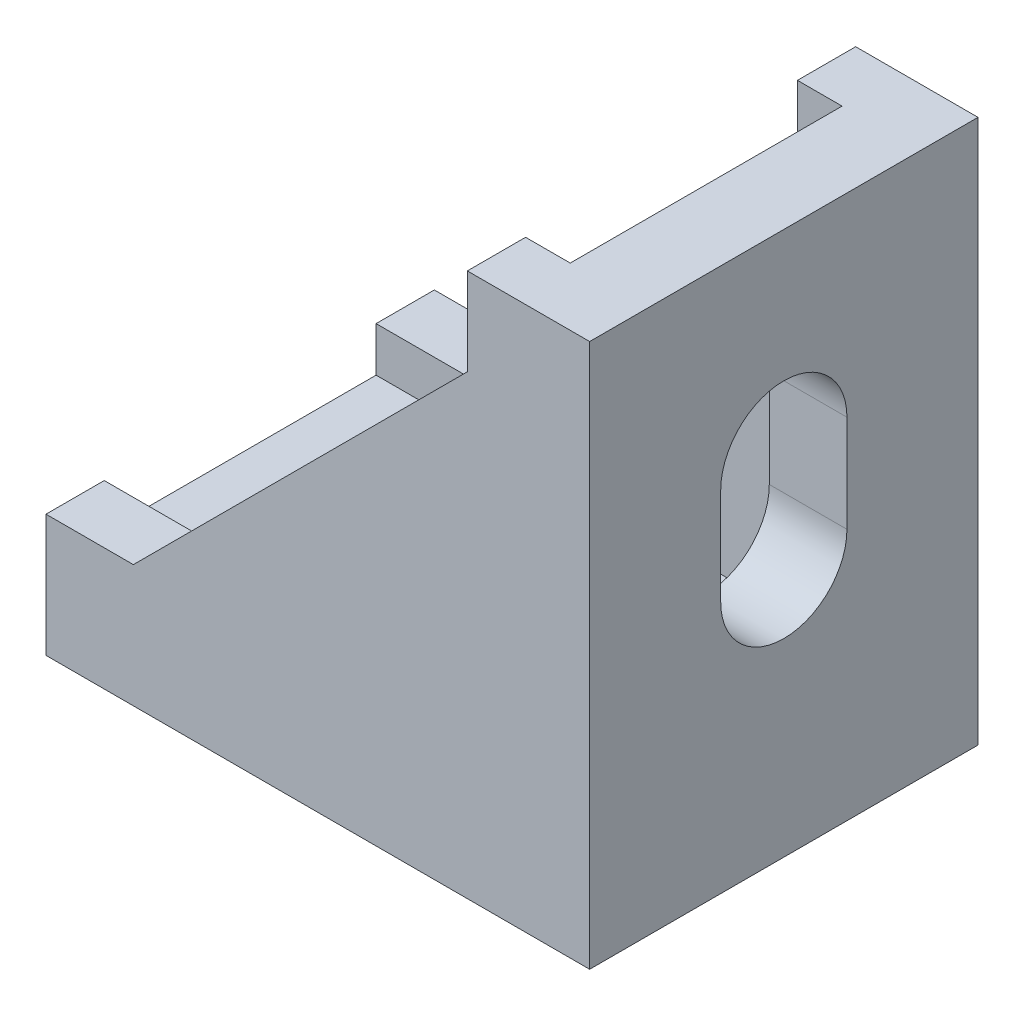
SolidWorks part; units mm, degrees
ref_plane "前视基准面" through (0, 0, 0) normal (0, 0, 1) x (1, 0, 0)
ref_plane "上视基准面" through (0, 0, 0) normal (0, 1, 0) x (1, 0, 0)
ref_plane "右视基准面" through (0, 0, 0) normal (1, 0, 0) x (0, 0, -1)
sketch "草图1" plane through (0, 0, 0) normal (0, 0, 1) x (1, 0, 0)
  line L1 (14, -14) -> (-14, -14)
  line L2 (14, -14) -> (14, 14)
  line L3 (14, 14) -> (10, 14)
  line L4 (-14, -14) -> (-14, -10)
  line L10 (10, 14) -> (10, -10)
  line L11 (10, -10) -> (-14, -10)
  point P0 (0, 0)
  dimension "D2" = 28
  dimension "D4" = 4
  dimension "D3" = 4
extrude "凸台-拉伸1" add sketch "草图1" along normal blind 20
sketch "草图3" plane through (0, 0, 0) normal (0, 0, -1) x (-1, 0, 0)
  line L0 (-10, 14) -> (-7.7, 14)
  line L1 (-7.7, 14) -> (-7.7, 9.5)
  line L2 (-7.7, 9.5) -> (9.5, -7.7)
  line L3 (9.5, -7.7) -> (14, -7.7)
  line L4 (14, -7.7) -> (14, -10)
  line L5 (-10, 14) -> (-14, 14)
  line L6 (-14, 14) -> (-14, -14)
  line L7 (-14, -14) -> (14, -14)
  line L8 (14, -14) -> (14, -10)
  dimension "D1" = 6.3
  dimension "D2" = 6.3
  dimension "D3" = 4.5
  dimension "D4" = 4.5
extrude "凸台-拉伸2" add sketch "草图3" against normal blind 3
ref_plane "基准面5" through (0, 0, 10) normal (0, 0, 1) x (1, 0, 0)
mirror "镜向2" about plane through (0, 0, 10) normal (0, 0, 1) of "凸台-拉伸2"
sketch "草图6" plane through (10, 0, 0) normal (-1, 0, 0) x (0, 0, 1)
  line L0 (10, 4) -> (10, -1) construction
  line L1 (10, -15.4) -> (10, 15.4) construction
  line L2 (13.25, 4) -> (13.25, -1)
  line L3 (6.75, 4) -> (6.75, -1)
  line L4 (20, -14) -> (0, -14) construction
  arc A0 (13.25, 4) -> (6.75, 4) centre (10, 4) ccw
  arc A1 (6.75, -1) -> (13.25, -1) centre (10, -1) ccw
  point P4 (10, 1.5)
  dimension "D1" = 6.5
  dimension "D2" = 5
  dimension "D3" = 13
extrude "切除-拉伸2" cut sketch "草图6" against normal through all
sketch "草图8" plane through (0, -10, 0) normal (0, 1, 0) x (1, 0, 0)
  line L0 (-4, -10) -> (1, -10) construction
  line L1 (-15.4, -10) -> (15.4, -10) construction
  line L2 (-4, -6.75) -> (1, -6.75)
  line L3 (-4, -13.25) -> (1, -13.25)
  line L4 (14, -20) -> (14, 0) construction
  arc A0 (-4, -6.75) -> (-4, -13.25) centre (-4, -10) ccw
  arc A1 (1, -13.25) -> (1, -6.75) centre (1, -10) ccw
  point P4 (-1.5, -10)
  dimension "D1" = 6.5
  dimension "D2" = 5
  dimension "D3" = 13
extrude "切除-拉伸3" cut sketch "草图8" against normal through all
